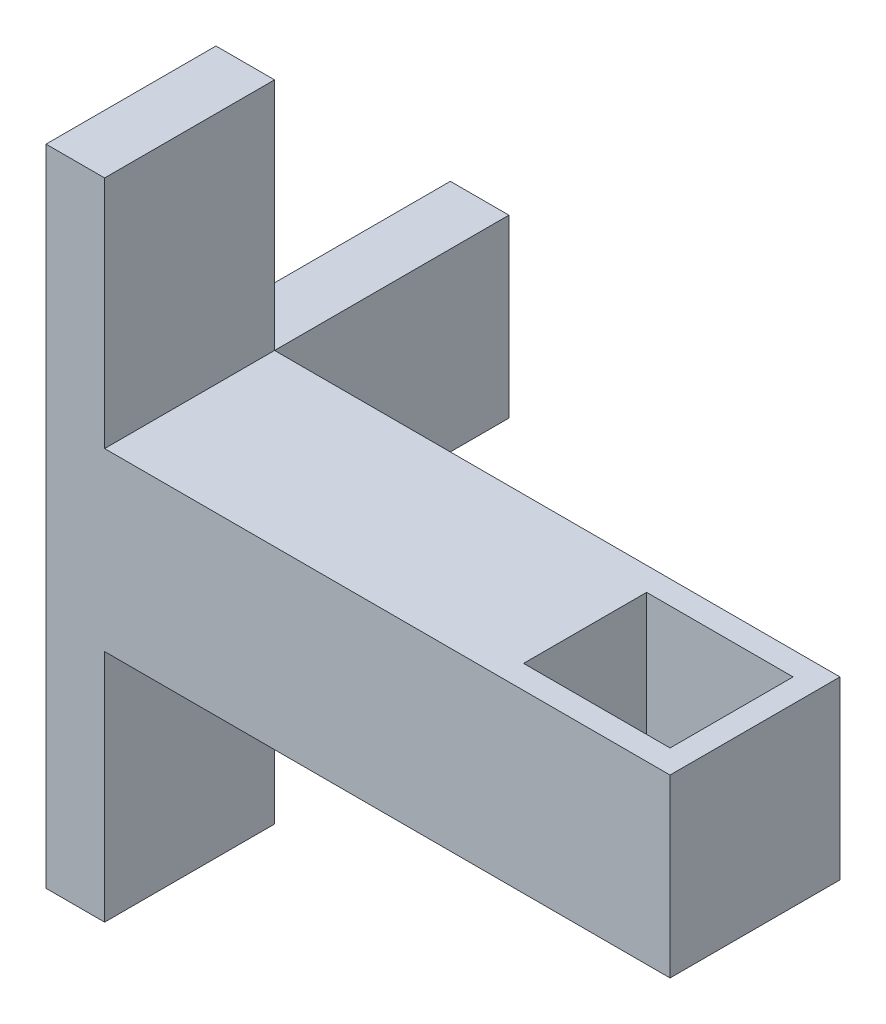
SolidWorks part; units mm, degrees
ref_plane "Front Plane" through (0, 0, 0) normal (0, 0, 1) x (1, 0, 0)
ref_plane "Top Plane" through (0, 0, 0) normal (0, 1, 0) x (1, 0, 0)
ref_plane "Right Plane" through (0, 0, 0) normal (1, 0, 0) x (0, 0, -1)
sketch "Sketch1" plane through (0, 0, 0) normal (0, 1, 0) x (1, 0, 0)
  line L1 (0, 0) -> (12.5, 0)
  line L2 (0, 0) -> (0, -10.5)
  line L3 (0, -10.5) -> (12.5, -10.5)
  line L4 (12.5, 0) -> (12.5, -10.5)
  line L5 (-2, -12.5) -> (14.5, -12.5)
  line L6 (14.5, 2) -> (14.5, -12.5)
  line L7 (-2, 2) -> (14.5, 2)
  line L8 (-2, 2) -> (-33.75, 2)
  line L9 (-33.75, 2) -> (-33.75, 22)
  line L10 (-33.75, 22) -> (-38.75, 22)
  line L11 (-38.75, 22) -> (-38.75, -12.5)
  line L14 (-36.75, -12.5) -> (-2, -12.5)
  line L15 (6.25, 0) -> (6.25, -10.5) construction
  line L16 (-36.75, -12.5) -> (-38.75, -12.5)
  line L17 (-2, 2) -> (-2, -12.5) construction
  dimension "D1" = 12.5
  dimension "D2" = 10.5
  dimension "D4" = 20
  dimension "D6" = 5
  dimension "D7" = 45
  dimension "D3" = 2
extrude "Boss-Extrude2" add sketch "Sketch1" along normal blind 15
sketch "Sketch3" plane through (-33.75, 0, 0) normal (1, 0, 0) x (0, 0, -1)
  line L0 (2, 15) -> (2, 35)
  line L1 (2, 35) -> (-12.5, 35)
  line L2 (-12.5, 35) -> (-12.5, -20)
  line L3 (-12.5, -20) -> (2, -20)
  line L4 (2, -20) -> (2, 15)
  dimension "D1" = 20
  dimension "D2" = 14.5
  dimension "D3" = 55
extrude "Boss-Extrude3" add sketch "Sketch3" against normal blind 5 contours L1 L2 L3 L4 L0
